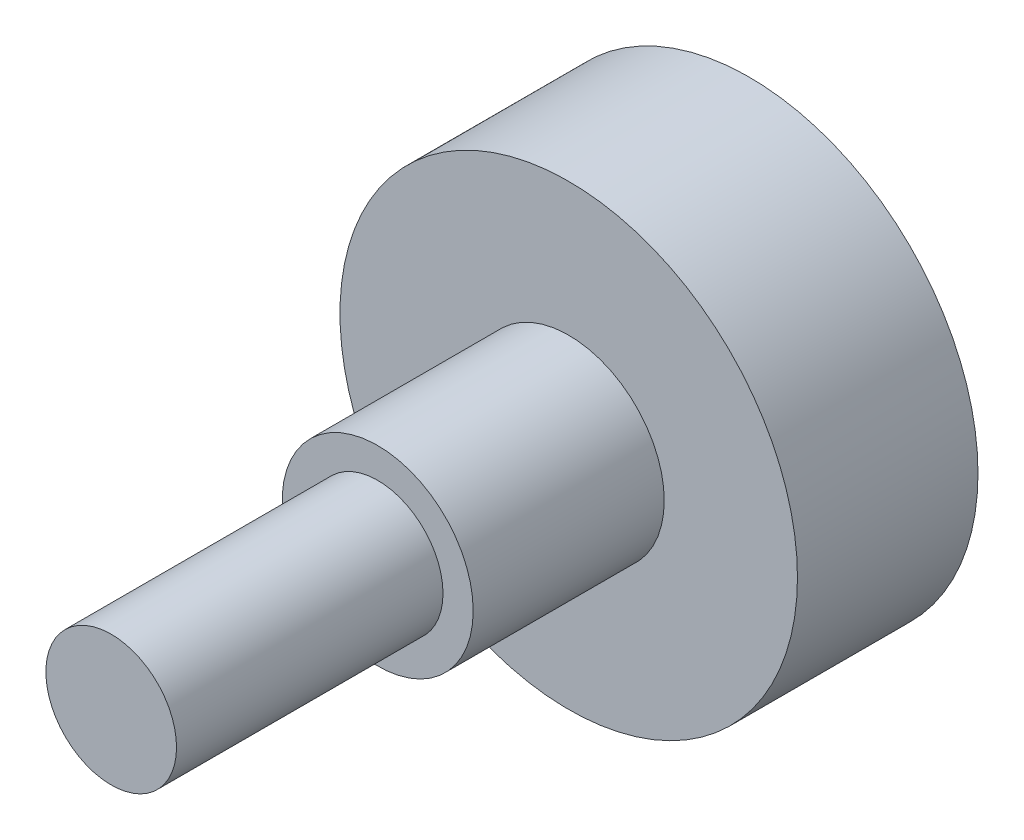
SolidWorks part; units mm, degrees
ref_plane "Front Plane" through (0, 0, 0) normal (0, 0, 1) x (1, 0, 0)
ref_plane "Top Plane" through (0, 0, 0) normal (0, 1, 0) x (1, 0, 0)
ref_plane "Right Plane" through (0, 0, 0) normal (1, 0, 0) x (0, 0, -1)
sketch "Sketch1" plane through (0, 0, 0) normal (0, 0, 1) x (1, 0, 0)
  circle A0 centre (0, 0) radius 11.1
  circle A1 centre (0, 0) radius 4.635
  circle A2 centre (0, 0) radius 3.17
  dimension "D1" = 22.2
  dimension "D2" = 9.27
  dimension "D3" = 6.34
extrude "Boss-Extrude1" add sketch "Sketch1" along normal blind 8.76 contours A0 A1
sketch "Sketch3" plane through (0, 0, 8.76) normal (0, 0, 1) x (1, 0, 0)
  circle A0 centre (0, 0) radius 4.635
extrude "Boss-Extrude2" add sketch "Sketch3" along normal blind 22.2 separate body
sketch "Sketch4" plane through (0, 0, 30.96) normal (0, 0, 1) x (1, 0, 0)
  circle A0 centre (0, 0) radius 3.17
  circle A1 centre (0, 0) radius 4.635
  dimension "D1" = 6.34
extrude "Cut-Extrude3" cut sketch "Sketch4" against normal blind 12.93
